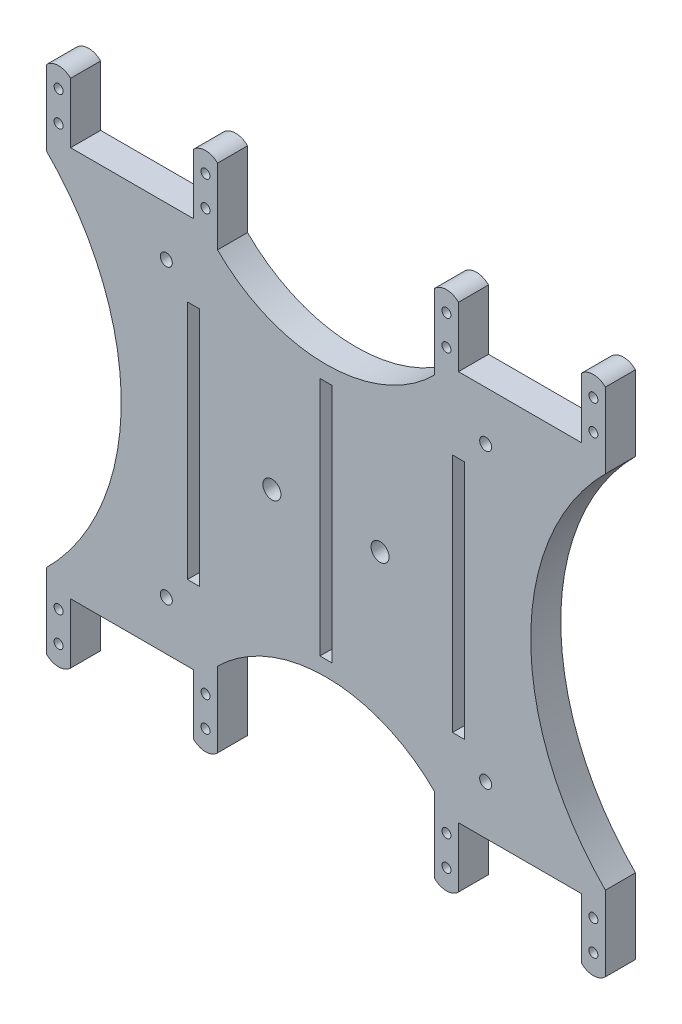
SolidWorks part; units mm, degrees
ref_plane "Front Plane" through (0, 0, 0) normal (0, 0, 1) x (1, 0, 0)
ref_plane "Top Plane" through (0, 0, 0) normal (0, 1, 0) x (1, 0, 0)
ref_plane "Right Plane" through (0, 0, 0) normal (1, 0, 0) x (0, 0, -1)
sketch "Sketch1" plane through (0, 0, 0) normal (0, 0, 1) x (1, 0, 0)
  line L0 (-100, 0) -> (68.1472, 0) construction
  line L5 (-85, 85) -> (85, -85) construction
  line L6 (-85, -85) -> (85, 85) construction
  line L7 (0, 100) -> (0, 85) construction
  line L8 (-85, -85) -> (-85, -65)
  line L10 (-85, 85) -> (-85, 65)
  line L11 (-85, 65) -> (-44.1, 65)
  line L12 (-44.1, 85) -> (-44.1, 65)
  line L14 (-44.1, -85) -> (-44.1, -65)
  line L15 (-85, -65) -> (-44.1, -65)
  line L16 (85, -85) -> (85, -65)
  line L18 (44.1, -85) -> (44.1, -65)
  line L19 (85, -65) -> (44.1, -65)
  line L20 (85, 65) -> (44.1, 65)
  line L22 (44.1, 85) -> (44.1, 65)
  line L23 (85, 85) -> (85, 65)
  line L24 (-87.5002, 79.9733) -> (93, -85) construction
  line L25 (46.1, -40) -> (42.1, -40)
  line L27 (-93, 85) -> (-93, 60)
  line L29 (93, 85) -> (93, 60)
  line L30 (-89.1611, 81.4913) -> (-89, 81.3441) construction
  line L31 (-93, -85) -> (93, 85) construction
  line L32 (-46.1, -40) -> (-42.1, -40)
  line L33 (-46.1, -40) -> (-46.1, 40)
  line L34 (-64.55, 87.1581) -> (-64.55, 70) construction
  line L35 (-89, 81.3441) -> (-89, 81.5) construction
  line L36 (-46.1, 40) -> (-42.1, 40)
  line L37 (-42.1, -40) -> (-42.1, 40)
  line L38 (-46.1, -40) -> (-42.1, 40) construction
  line L39 (-46.1, 40) -> (-42.1, -40) construction
  line L40 (46.1, 40) -> (42.1, 40)
  line L41 (46.1, -40) -> (46.1, 40)
  line L42 (42.1, -40) -> (42.1, 40)
  line L44 (-2, -40) -> (2, -40)
  line L45 (-2, -40) -> (-2, 40)
  line L46 (-2, 40) -> (2, 40)
  line L47 (2, -40) -> (2, 40)
  line L48 (-93, 65) -> (-93, 60)
  line L49 (-93, -65) -> (-93, -60)
  line L50 (-2, -40) -> (2, 40) construction
  line L51 (-36.1, -85) -> (-36.1, -60)
  line L52 (-2, 40) -> (2, -40) construction
  line L53 (36.1, -85) -> (36.1, -60)
  line L54 (36.1, 85) -> (36.1, 60)
  line L55 (-36.1, 85) -> (-36.1, 60)
  line L60 (93, -65) -> (93, -60)
  line L61 (93, 65) -> (93, 60)
  line L62 (-93, -60) -> (-93, -85)
  line L63 (93, -60) -> (93, -85)
  line L64 (93, 0) -> (100, 0) construction
  line L66 (0, -85) -> (0, -100) construction
  line L68 (0, 45.0469) -> (0, -45.0469) construction
  line L69 (-64.55, -65) -> (-64.55, -85) construction
  arc A0 (-93, 60) -> (-93, -60) centre (-153, 0) cw
  arc A1 (-36.1, -60) -> (36.1, -60) centre (0, -96.1) cw
  arc A2 (-36.1, 60) -> (36.1, 60) centre (0, 96.1) ccw
  arc A3 (93, 60) -> (93, -60) centre (153, 0) ccw
  arc A4 (-93, 85) -> (-85, 85) centre (-89, 81) cw
  arc A5 (-44.1, 85) -> (-36.1, 85) centre (-40.1, 81) cw
  arc A6 (-93, -85) -> (-85, -85) centre (-89, -81) ccw
  arc A7 (-44.1, -85) -> (-36.1, -85) centre (-40.1, -81) ccw
  arc A8 (44.1, -85) -> (36.1, -85) centre (40.1, -81) cw
  arc A9 (93, -85) -> (85, -85) centre (89, -81) cw
  arc A10 (44.1, 85) -> (36.1, 85) centre (40.1, 81) ccw
  arc A11 (93, 85) -> (85, 85) centre (89, 81) ccw
  circle A12 centre (-89, 70) radius 1.5
  circle A13 centre (-89, 80) radius 1.5
  circle A14 centre (-40.1, 70) radius 1.5
  circle A15 centre (-40.1, 80) radius 1.5
  circle A16 centre (-40.1, -70) radius 1.5
  circle A17 centre (-40.1, -80) radius 1.5
  circle A18 centre (-89, -80) radius 1.5
  circle A19 centre (-89, -70) radius 1.5
  circle A20 centre (89, 80) radius 1.5
  circle A21 centre (89, 70) radius 1.5
  circle A22 centre (40.1, 80) radius 1.5
  circle A23 centre (40.1, 70) radius 1.5
  circle A24 centre (89, -70) radius 1.5
  circle A25 centre (89, -80) radius 1.5
  circle A26 centre (40.1, -80) radius 1.5
  circle A27 centre (40.1, -70) radius 1.5
  point P0 (0, 0)
  point P10 (-64.55, 75)
  point P27 (0, 0)
  point P102 (-44.1, 0)
  point P111 (0, 0)
  dimension "D1" = 4
  dimension "D2" = 80
  dimension "D3" = 40.9
  dimension "D4" = 20
  dimension "D5" = 4
  dimension "D6" = 80
extrude "Boss-Extrude1" add sketch "Sketch1" along normal blind 10 contours L29 A11 L23 L20 L22 A10 L54 A2 L55 A5 L12 L11 L10 A4 L27 A0 L49 L62 A6 L8 L15 L14 A7 L51 A1 L53 A8 L18 L19 L16 A9 L63 L60 A3
sketch "Sketch2" plane through (0, 0, 10) normal (0, 0, 1) x (1, 0, 0)
  line L0 (36.1, -60) -> (53.15, -60)
  line L1 (53.15, -60) -> (53.15, -48.68)
  circle A0 centre (53.15, -48.68) radius 2
  circle A1 centre (-53.15, -48.68) radius 2
  circle A2 centre (53.15, 48.68) radius 2
  circle A3 centre (-53.15, 48.68) radius 2
  dimension "D1" = 11.32
  dimension "D2" = 17.05
extrude "Cut-Extrude1" cut sketch "Sketch2" against normal blind 20 and the other way through all
sketch "Sketch3" plane through (0, 0, 10) normal (0, 0, 1) x (1, 0, 0)
  line L0 (15, 0) -> (18, 0)
  line L2 (-15, 0) -> (-18, 0)
  circle A0 centre (18, 0) radius 3
  circle A1 centre (-18, 0) radius 3
extrude "Cut-Extrude2" cut sketch "Sketch3" against normal blind 20
